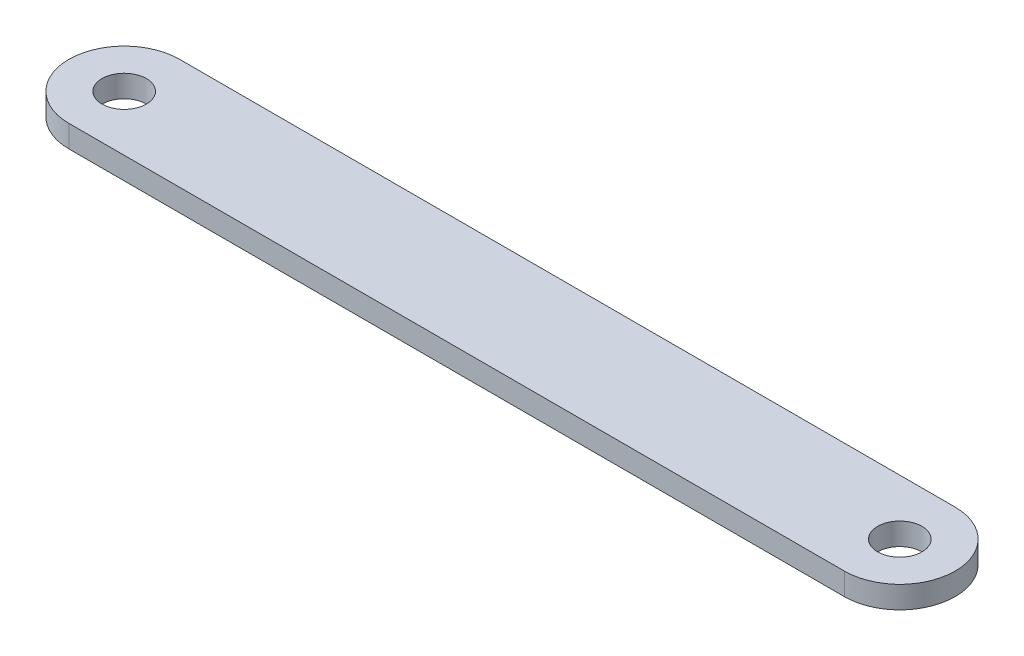
SolidWorks part; units mm, degrees
ref_plane "Front Plane" through (0, 0, 0) normal (0, 0, 1) x (1, 0, 0)
ref_plane "Top Plane" through (0, 0, 0) normal (0, 1, 0) x (1, 0, 0)
ref_plane "Right Plane" through (0, 0, 0) normal (1, 0, 0) x (0, 0, -1)
sketch "Sketch1" plane through (0, 0, 0) normal (0, 1, 0) x (1, 0, 0)
  line L1 (0, 0) -> (88.9, 0)
  line L3 (0, 12.7) -> (88.9, 12.7)
  arc A0 (0, 12.7) -> (0, 0) centre (0, 6.35) ccw
  arc A1 (88.9, 12.7) -> (88.9, 0) centre (88.9, 6.35) cw
  circle A2 centre (0, 6.35) radius 2.54
  circle A3 centre (88.9, 6.35) radius 2.54
  dimension "D3" = 5.08
  dimension "D4" = 5.08
  dimension "D1" = 88.9
  dimension "D2" = 12.7
extrude "Boss-Extrude2" add sketch "Sketch1" along normal blind 2.54
